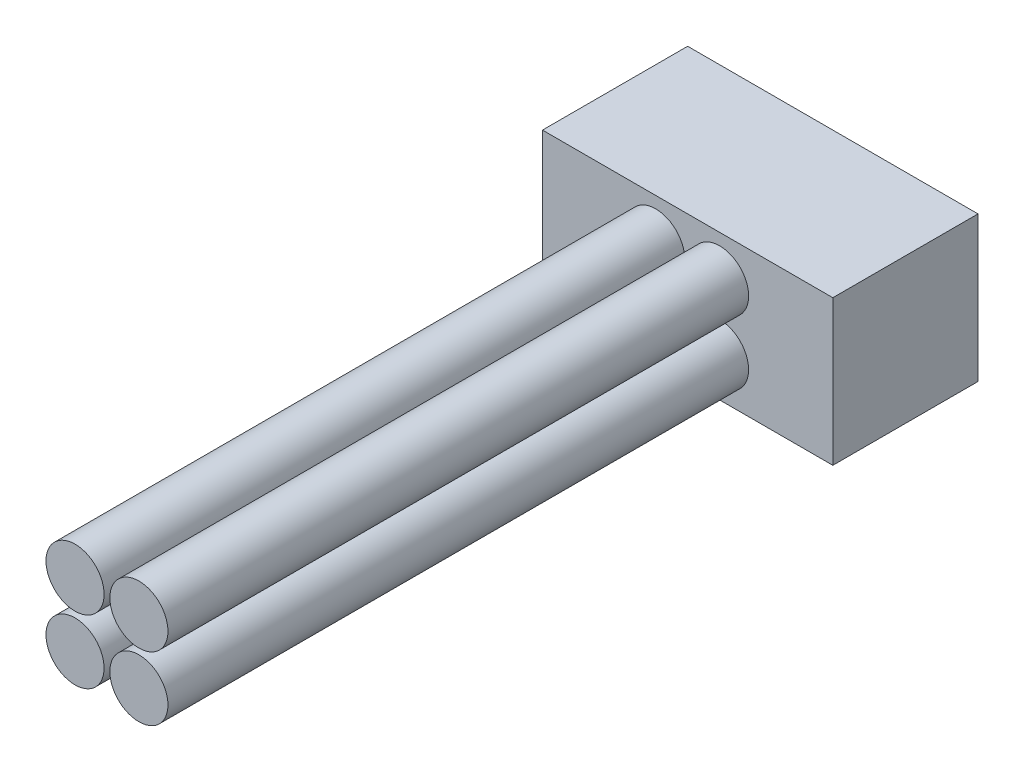
SolidWorks part; units mm, degrees
ref_plane "Front Plane" through (0, 0, 0) normal (0, 0, 1) x (1, 0, 0)
ref_plane "Top Plane" through (0, 0, 0) normal (0, 1, 0) x (1, 0, 0)
ref_plane "Right Plane" through (0, 0, 0) normal (1, 0, 0) x (0, 0, -1)
sketch "Sketch1" plane through (0, 0, 0) normal (0, 0, 1) x (1, 0, 0)
  line L1 (0, 0) -> (10, 0)
  line L2 (0, 0) -> (0, 5)
  line L3 (0, 5) -> (10, 5)
  line L4 (10, 0) -> (10, 5)
  dimension "D1" = 10
  dimension "D2" = 5
extrude "Boss-Extrude1" add sketch "Sketch1" along normal blind 5
sketch "Sketch2" plane through (0, 0, 5) normal (0, 0, 1) x (1, 0, 0)
  line L0 (5, 5) -> (5, 0) construction
  line L1 (10, 5) -> (0, 5) construction
  line L2 (0, 0) -> (10, 0) construction
  line L3 (0, 0) -> (10, 0)
  circle A0 centre (6.1, 3.6) radius 1
  circle A1 centre (3.9, 3.6) radius 1
  circle A2 centre (3.9, 1.4) radius 1
  circle A3 centre (6.1, 1.4) radius 1
extrude "Boss-Extrude2" add sketch "Sketch2" along normal blind 20 contours A1 | A0 | A2 | A3
